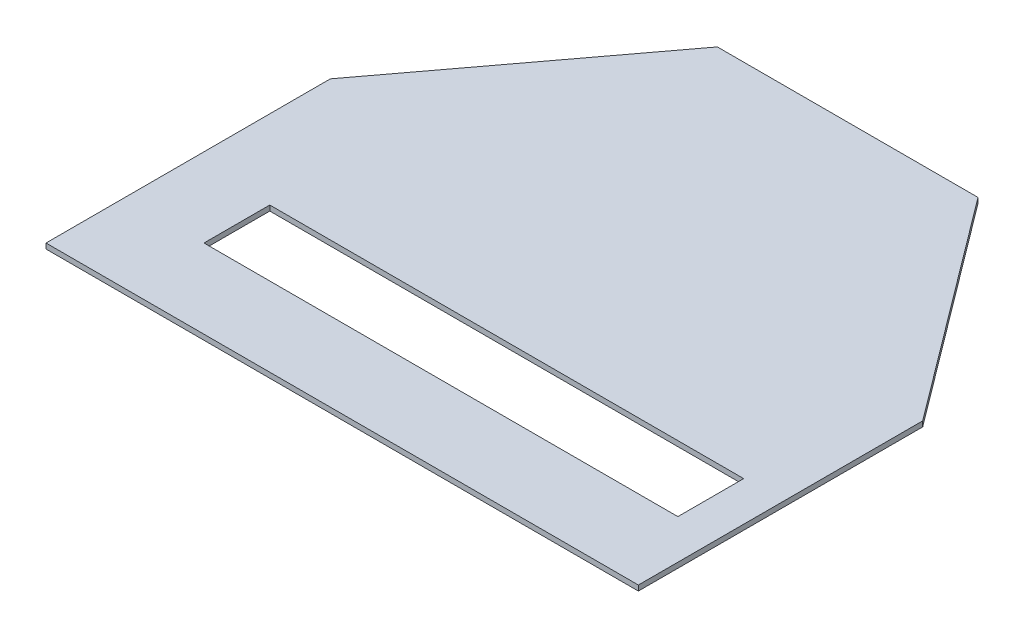
SolidWorks part; units mm, degrees
material "ABS PC"
ref_plane "前视基准面" through (0, 0, 0) normal (0, 0, 1) x (1, 0, 0)
ref_plane "上视基准面" through (0, 0, 0) normal (0, 1, 0) x (1, 0, 0)
ref_plane "右视基准面" through (0, 0, 0) normal (1, 0, 0) x (0, 0, -1)
sketch "草图1" plane through (0, 0, 0) normal (0, 1, 0) x (1, 0, 0)
  line L0 (0, 0) -> (0, 384) construction
  line L1 (-225, 0) -> (225, 0)
  line L2 (225, 0) -> (225, 216)
  line L3 (225, 216) -> (99, 384)
  line L4 (99, 384) -> (-99, 384)
  line L5 (-225, 0) -> (-225, 216)
  line L6 (-225, 216) -> (-99, 384)
  line L7 (0, 384) -> (309, 384) construction
  line L8 (0, 0) -> (441, 0) construction
  circle A0 centre (99, 384) radius 210 construction
  circle A1 centre (225, 0) radius 216 construction
  point P8 (0, 0)
  dimension "D1" = 198
  dimension "D2" = 216
  dimension "D3" = 384
  dimension "D4" = 450
  dimension "D5" = 210
extrude "凸台-拉伸1" add sketch "草图1" along normal blind 4
sketch "草图2" plane through (0, 4, 0) normal (0, 1, 0) x (1, 0, 0)
  line L0 (225, 0) -> (225, 216) construction
  line L1 (-165, 110) -> (195, 110)
  line L2 (-165, 110) -> (-165, 60)
  line L3 (-165, 60) -> (195, 60)
  line L4 (195, 110) -> (195, 60)
  line L5 (-225, 0) -> (225, 0) construction
  dimension "D1" = 30
  dimension "D2" = 360
  dimension "D3" = 50
  dimension "D4" = 60
extrude "切除-拉伸1" cut sketch "草图2" against normal up to next
